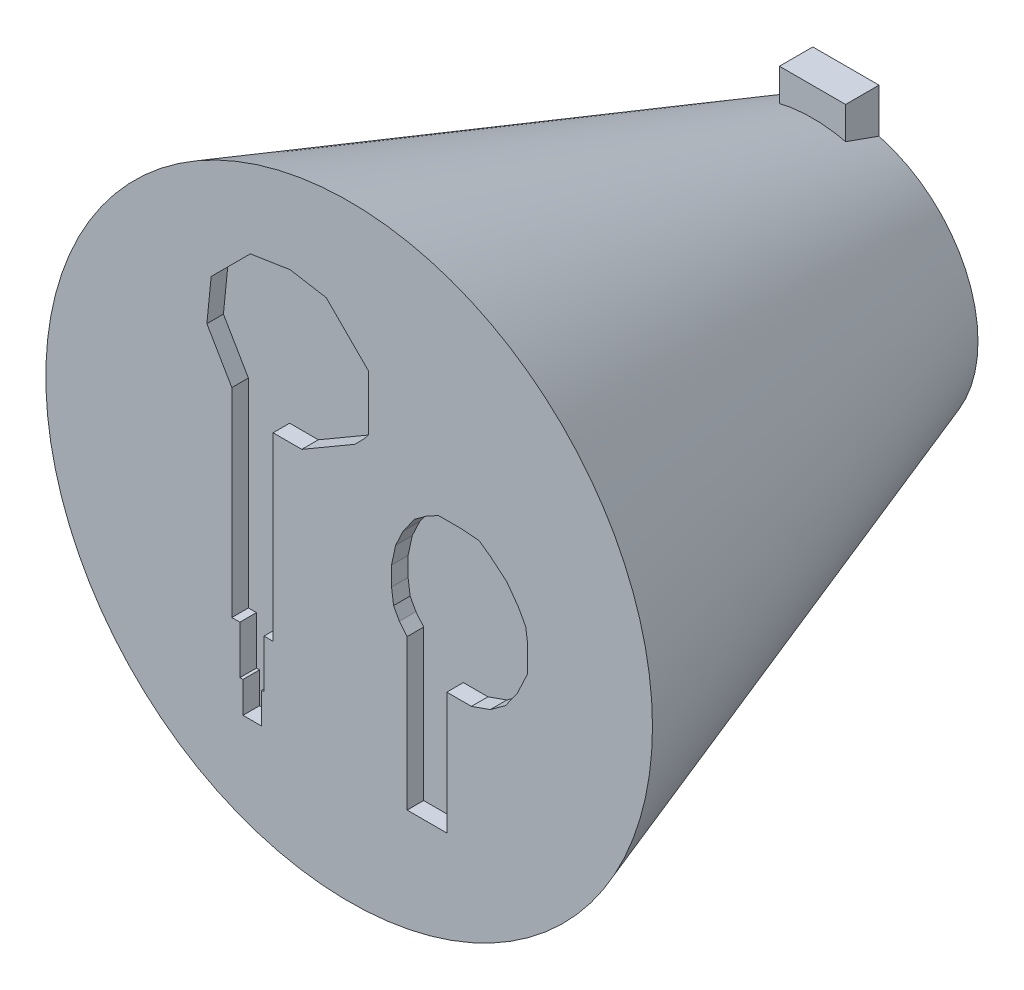
SolidWorks part; units mm, degrees
ref_plane "Plan de face" through (0, 0, 0) normal (0, 0, 1) x (1, 0, 0)
ref_plane "Plan de dessus" through (0, 0, 0) normal (0, 1, 0) x (1, 0, 0)
ref_plane "Plan de droite" through (0, 0, 0) normal (1, 0, 0) x (0, 0, -1)
sketch "Esquisse1" plane through (0, 0, 0) normal (0, 0, 1) x (1, 0, 0)
  circle A0 centre (-45.6455, 34.7889) radius 4
  dimension "D1" = 8
extrude "Boss.-Extru.1" add sketch "Esquisse1" along normal blind 15 draft 19 draft outward yes
sketch "Esquisse2" plane through (0, 0, 0) normal (0, 0, -1) x (-1, 0, 0)
  line L0 (49.6455, 34.7889) -> (41.6455, 34.7889) construction
  line L1 (45.6455, 38.7889) -> (45.6455, 30.7889) construction
  line L2 (46.7521, 44.793) -> (46.9926, 44.5429) construction
  line L4 (44.6455, 34.7889) -> (46.6455, 34.7889)
  line L5 (44.6455, 34.7889) -> (44.6455, 39.9889)
  line L6 (44.6455, 39.9889) -> (46.6455, 39.9889)
  line L7 (46.6455, 34.7889) -> (46.6455, 39.9889)
  circle A0 centre (45.6455, 34.7889) radius 4 construction
  dimension "D1" = 5.2
  dimension "D2" = 1
  dimension "D3" = 2
extrude "Boss.-Extru.2" add sketch "Esquisse2" along normal blind 0.01 and the other way blind 1 separate body
sketch "Esquisse4" plane through (0, 0, 15) normal (0, 0, 1) x (1, 0, 0)
  line L0 (-49.1896, 37.3078) -> (-49.1896, 31.2917)
  line L1 (-47.9431, 36.749) -> (-47.9431, 31.2917)
  line L2 (-49.1896, 31.2917) -> (-47.9431, 31.2917)
  line L3 (-48.947, 29.8398) -> (-48.2184, 29.8398)
  line L4 (-48.2184, 31.2917) -> (-48.2184, 29.8398)
  line L5 (-48.947, 31.2917) -> (-48.947, 29.8398)
  line L6 (-48.8535, 29.8398) -> (-48.8535, 28.901)
  line L7 (-48.286, 29.8398) -> (-48.286, 28.901)
  line L8 (-48.8535, 28.901) -> (-48.286, 28.901)
  line L9 (-43.8935, 33.441) -> (-43.8935, 28.901)
  line L10 (-42.6961, 32.5861) -> (-42.6961, 28.901)
  line L11 (-43.8935, 28.901) -> (-42.6961, 28.901)
  line L12 (-46.3395, 39.3422) -> (-46.3395, 38.7948)
  line L13 (-46.3395, 38.7948) -> (-46.0788, 38.7948)
  line L14 (-42.5724, 34.6667) -> (-42.5724, 35.1668)
  line L15 (-42.3399, 34.6667) -> (-42.3953, 34.8522)
  line L16 (-42.5724, 34.8522) -> (-42.3953, 34.8522)
  line L17 (-42.3953, 34.8522) -> (-42.3308, 34.9167)
  line L18 (-42.3308, 34.9167) -> (-42.3308, 35.0769)
  line L19 (-42.3308, 35.0769) -> (-42.4207, 35.1668)
  line L20 (-42.4207, 35.1668) -> (-42.5724, 35.1668)
  line L21 (-49.1896, 37.3078) -> (-49.944, 38.6032)
  line L22 (-49.944, 38.6032) -> (-49.814, 39.9035)
  line L23 (-49.814, 39.9035) -> (-48.6303, 41.0872)
  line L24 (-48.6303, 41.0872) -> (-47.4325, 41.2727)
  line L25 (-47.4325, 41.2727) -> (-46.3395, 41.0872)
  line L26 (-46.3395, 41.0872) -> (-45.3066, 40.0543)
  line L27 (-47.9431, 36.749) -> (-47.0759, 36.749)
  line L28 (-47.0759, 36.749) -> (-46.407, 37.1385)
  line L29 (-46.407, 37.1385) -> (-45.4779, 37.6796)
  line L30 (-45.4779, 37.6796) -> (-45.202, 37.9555)
  line L31 (-45.3066, 40.0543) -> (-45.5518, 39.809)
  line L32 (-45.5518, 39.809) -> (-45.5518, 38.3053)
  line L33 (-45.5518, 38.3053) -> (-45.202, 37.9555)
  line L34 (-45.3066, 40.0543) -> (-45.0613, 39.809)
  line L35 (-45.0613, 39.809) -> (-45.0613, 38.1304)
  line L36 (-45.0613, 38.1304) -> (-45.202, 37.9555)
  line L37 (-43.5658, 35.8496) -> (-43.8935, 35.6564)
  line L38 (-43.8935, 35.6564) -> (-43.9869, 35.2952)
  line L39 (-43.9869, 35.2952) -> (-43.9869, 34.3481)
  line L40 (-43.9869, 34.3481) -> (-43.7717, 33.983)
  line L41 (-43.7717, 33.983) -> (-43.5658, 33.983)
  line L42 (-43.5658, 33.983) -> (-43.2561, 34.1656)
  line L43 (-43.2561, 34.1656) -> (-43.2561, 35.6564)
  line L44 (-43.3071, 35.6985) -> (-43.5658, 35.8496)
  line L45 (-43.2561, 35.6564) -> (-43.3071, 35.6985)
  line L46 (-41.1331, 34.6245) -> (-40.608, 34.6245)
  line L47 (-40.608, 34.6245) -> (-40.5307, 34.7017)
  line L48 (-40.5307, 34.7017) -> (-40.5307, 34.9953)
  line L49 (-40.5307, 34.9953) -> (-40.6706, 35.1351)
  line L50 (-40.6706, 35.1668) -> (-41.1331, 35.1668)
  line L51 (-41.1331, 35.1668) -> (-41.257, 35.0429)
  line L52 (-41.257, 35.0429) -> (-41.257, 34.8029)
  line L53 (-41.257, 34.8029) -> (-41.1331, 34.6245)
  line L54 (-43.8935, 33.441) -> (-42.6961, 32.5861)
  line L55 (-42.6961, 32.5861) -> (-41.9515, 32.5861)
  line L56 (-41.9515, 32.5861) -> (-41.3782, 32.79)
  line L57 (-41.3782, 32.79) -> (-40.9222, 33.1202)
  line L58 (-40.9222, 33.1202) -> (-40.5652, 33.6202)
  line L59 (-40.5652, 33.6202) -> (-40.31, 34.1656)
  line L60 (-40.31, 34.1656) -> (-40.2618, 34.2686)
  line L61 (-40.2618, 34.2686) -> (-40.2618, 35.1351)
  line L62 (-40.2618, 35.1351) -> (-40.31, 35.4884)
  line L63 (-40.31, 35.4884) -> (-40.5307, 35.8941)
  line L64 (-40.5307, 35.8941) -> (-40.8871, 36.3863)
  line L65 (-40.8871, 36.3863) -> (-41.3782, 36.7964)
  line L66 (-41.3782, 36.7964) -> (-41.7233, 37.0428)
  line L67 (-41.7233, 37.0428) -> (-42.2822, 37.0819)
  line L68 (-42.2822, 37.0819) -> (-42.9047, 37.0819)
  line L69 (-42.9455, 37.0819) -> (-43.3071, 36.8852)
  line L70 (-43.3071, 36.8852) -> (-43.6696, 36.6228)
  line L71 (-43.6696, 36.6228) -> (-44.0141, 36.1402)
  line L72 (-44.0141, 36.1402) -> (-44.2405, 35.6564)
  line L73 (-44.2405, 35.6564) -> (-44.3649, 35.0769)
  line L74 (-44.3649, 35.0769) -> (-44.3649, 34.5021)
  line L75 (-44.3649, 34.5021) -> (-44.3027, 34.0466)
  line L76 (-44.3027, 34.0466) -> (-44.1273, 33.7242)
  line L77 (-44.1273, 33.7242) -> (-43.8935, 33.441)
  line L78 (-40.6706, 35.1668) -> (-40.6706, 35.1351)
  line L79 (-41.9515, 32.5861) -> (-42.6961, 32.5861)
  line L80 (-44.1273, 33.7242) -> (-43.8935, 33.441)
  line L81 (-44.3649, 35.0769) -> (-44.3649, 34.5021)
  line L82 (-42.9455, 37.0819) -> (-42.9047, 37.0819)
  line L83 (-48.947, 38.7948) -> (-48.0395, 38.7948)
  line L84 (-48.0395, 38.7948) -> (-47.8551, 38.8951)
  line L85 (-47.8551, 38.8951) -> (-47.8551, 39.1725)
  line L86 (-47.8551, 39.1725) -> (-47.9473, 39.3419)
  line L87 (-47.9473, 39.3419) -> (-48.8535, 39.3419)
  line L88 (-48.8535, 39.3419) -> (-49.0092, 39.2572)
  line L89 (-49.0092, 39.2572) -> (-49.0092, 39.0338)
  line L90 (-49.0092, 39.0338) -> (-48.947, 38.7948)
extrude "Enlèv. mat.-Extru.2" cut sketch "Esquisse4" against normal blind 0.5
